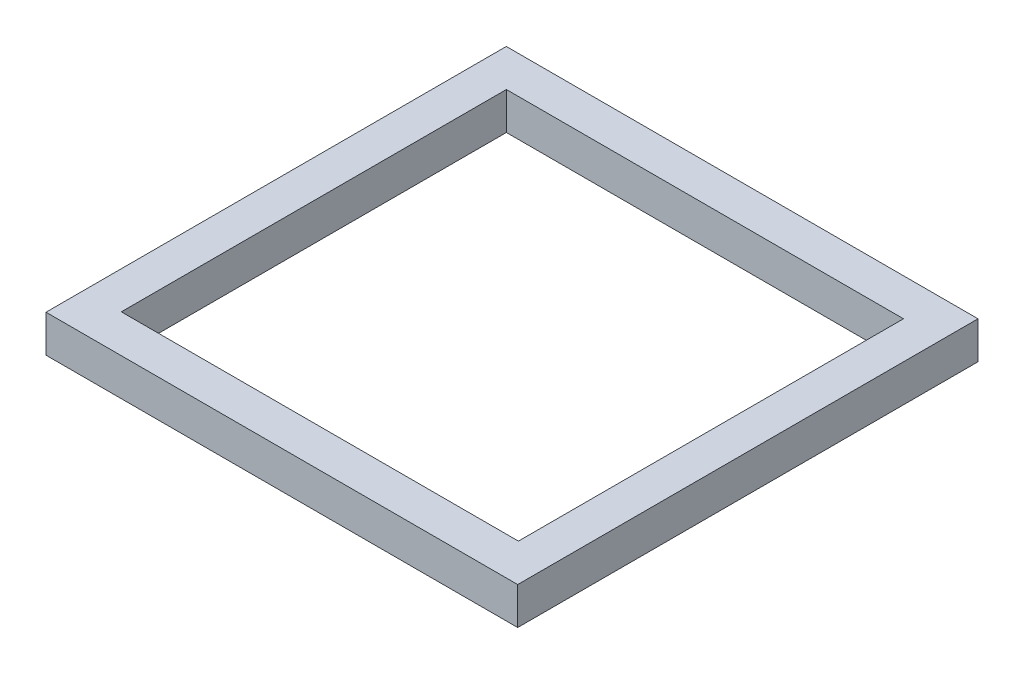
SolidWorks part; units mm, degrees
ref_plane "Front Plane" through (0, 0, 0) normal (0, 0, 1) x (1, 0, 0)
ref_plane "Top Plane" through (0, 0, 0) normal (0, 1, 0) x (1, 0, 0)
ref_plane "Right Plane" through (0, 0, 0) normal (1, 0, 0) x (0, 0, -1)
sketch "Sketch1" plane through (0, 0, 0) normal (0, 1, 0) x (1, 0, 0)
  line L0 (0, 0) -> (0, 0.5) construction
  line L1 (0, 0) -> (0, 500) construction
  line L2 (0, 0.5) -> (500, 0.5) construction
  line L3 (0, 0) -> (-566.2718, 0) construction
  line L4 (0, 0.5) -> (0, -535.7041) construction
  line L5 (0, 500) -> (0, 600) construction
  line L6 (-566.0727, 500) -> (500, 500)
  line L7 (-566.0727, 500) -> (-566.0727, -533.7479)
  line L8 (-566.0727, -533.7479) -> (500, -533.7479)
  line L9 (500, 500) -> (500, -533.7479)
  line L10 (-566.2718, 0) -> (-666.2718, 0) construction
  line L11 (0, -535.7041) -> (0, -635.7041) construction
  line L12 (500, 0.5) -> (600, 0.5) construction
  line L14 (-666.2718, 600) -> (600, 600)
  line L15 (-666.2718, 600) -> (-666.2718, -635.7041)
  line L16 (-666.2718, -635.7041) -> (600, -635.7041)
  line L17 (600, 600) -> (600, -635.7041)
  dimension "D1" = 100
extrude "Boss-Extrude1" add sketch "Sketch1" along normal blind 100
